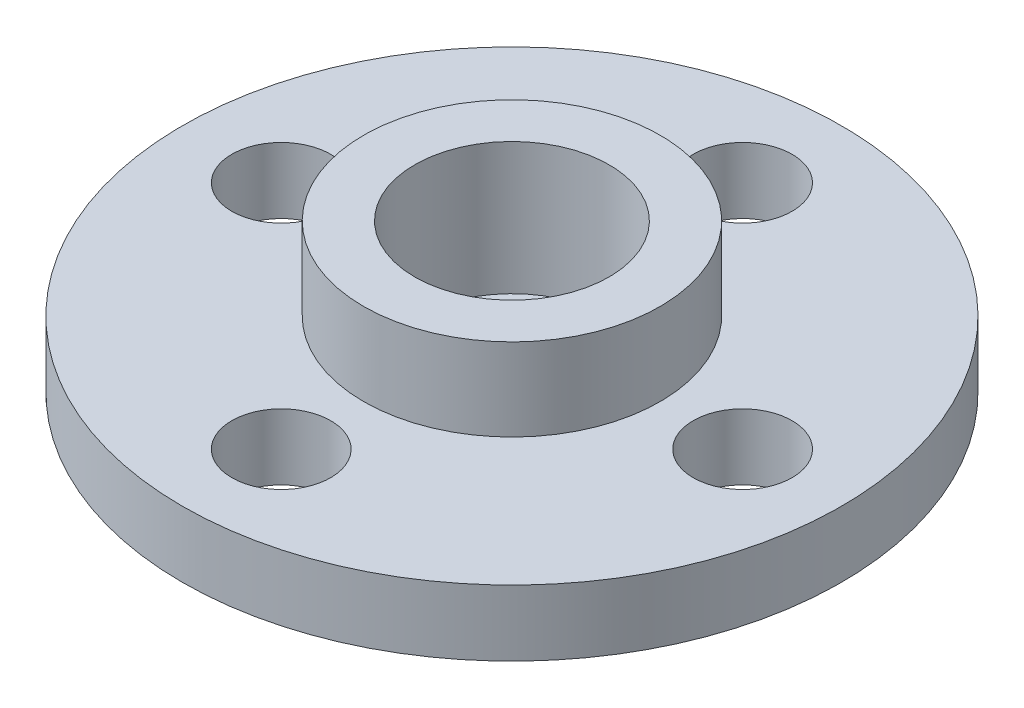
SolidWorks part; units mm, degrees
material "1060 合金"
ref_plane "前视基准面" through (0, 0, 0) normal (0, 0, 1) x (1, 0, 0)
ref_plane "上视基准面" through (0, 0, 0) normal (0, 1, 0) x (1, 0, 0)
ref_plane "右视基准面" through (0, 0, 0) normal (1, 0, 0) x (0, 0, -1)
sketch "草图1" plane through (0, 0, 0) normal (0, 1, 0) x (1, 0, 0)
  circle A0 centre (0, 0) radius 10
  dimension "D1" = 20
extrude "凸台-拉伸1" add sketch "草图1" along normal blind 2
sketch "草图2" plane through (0, 2, 0) normal (0, 1, 0) x (1, 0, 0)
  circle A0 centre (0, 0) radius 4.5
  dimension "D1" = 9
extrude "凸台-拉伸2" add sketch "草图2" along normal blind 2.5
sketch "草图3" plane through (0, 4.5, 0) normal (0, 1, 0) x (1, 0, 0)
  circle A0 centre (0, 0) radius 2.95
  dimension "D1" = 5.9
extrude "切除-拉伸1" cut sketch "草图3" against normal blind 4
hole_wizard "Ø3.0 (3) 直径孔1" positions "草图5" profile "草图4" hole size "Ø3.0" standard "GB" end condition through all
sketch "草图5" plane through (0, 2, 0) normal (0, 1, 0) x (1, 0, 0)
  point P0 (0, 7)
  point P13 (7, 0)
  point P14 (0, -7)
  point P15 (-7, 0)
  point P16 (0, 0)
  dimension "D1" = 7
  dimension "D2" = 4
sketch "草图4" plane through (0, 2, -7) normal (1, 0, 0) x (0, 0, 1)
  line L0 (0, 0) -> (0, 2)
  line L1 (0, 2) -> (1.5, 2)
  line L2 (1.5, 2) -> (1.5, 0)
  line L5 (1.5, 0) -> (0, 0)
  line L11 (0, -6.35) -> (0, 107.95) construction
  dimension "通孔孔直径" = 3
  dimension "通孔孔深度" = 2
